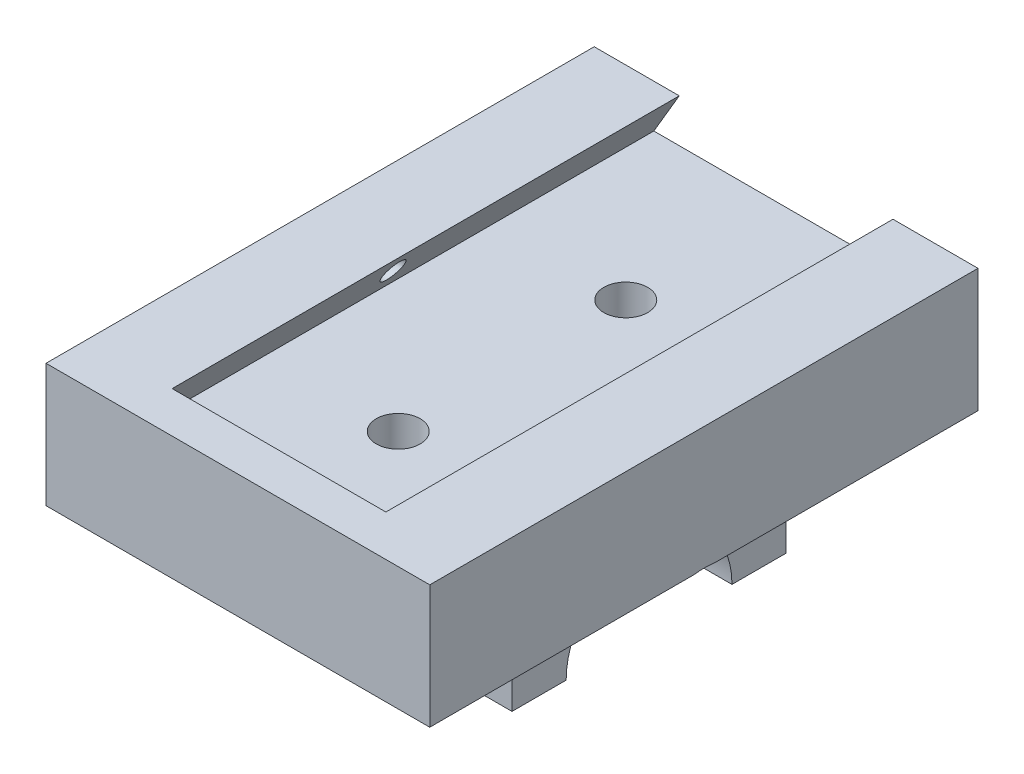
SolidWorks part; units mm, degrees
ref_plane "Front Plane" through (0, 0, 0) normal (0, 0, 1) x (1, 0, 0)
ref_plane "Top Plane" through (0, 0, 0) normal (0, 1, 0) x (1, 0, 0)
ref_plane "Right Plane" through (0, 0, 0) normal (1, 0, 0) x (0, 0, -1)
sketch "Sketch1" plane through (0, 0, 0) normal (0, 0, 1) x (1, 0, 0)
  line L0 (-28, 0) -> (28, 0)
  line L1 (28, 0) -> (28, 18)
  line L2 (28, 18) -> (-28, 18)
  line L3 (-28, 18) -> (-28, 0)
extrude "Channel Block" add sketch "Sketch1" along normal mid plane 80
sketch "Sketch2" plane through (0, 0, 0) normal (1, 0, 0) x (0, 0, -1)
  line L0 (-20, -12) -> (20, -12)
  line L1 (20, -12) -> (20, 0.5)
  line L2 (20, 0.5) -> (-20, 0.5)
  line L3 (-20, 0.5) -> (-20, -12)
extrude "Clamp Upper Half" add sketch "Sketch2" along normal mid plane 40
sketch "Sketch3" plane through (0, 0, 0) normal (0, 0, 1) x (1, 0, 0)
  line L0 (-15.3, 18.5) -> (15.3, 18.5)
  line L1 (15.3, 18.5) -> (19.3, 11.7)
  line L2 (19.3, 11.7) -> (-19.3, 11.7)
  line L3 (-19.3, 11.7) -> (-15.3, 18.5)
extrude "Dovetail Channel" cut sketch "Sketch3" against normal blind 41 and the other way blind 34
sketch "Sketch4" plane through (0, 0, 0) normal (1, 0, 0) x (0, 0, -1)
  circle A0 centre (0, -12) radius 12.1
extrude "Handlebar Bore" cut sketch "Sketch4" against normal through all and the other way through all
sketch "Sketch5" plane through (0, 0, 0) normal (0, 1, 0) x (1, 0, 0)
  circle A0 centre (0, -16.6) radius 3.2
  circle A1 centre (0, 16.6) radius 3.2
extrude "M5 Insert Holes" cut sketch "Sketch5" against normal through all and the other way through all
sketch "Sketch6" plane through (0, 0, 0) normal (1, 0, 0) x (0, 0, -1)
  circle A0 centre (0, 15) radius 1.65
extrude "Lock Screw Hole" cut sketch "Sketch6" against normal through all
equation "\"BrW\" = 56.0"
equation "\"BrL\" = 80.0"
equation "\"BrH\" = 18.0"
equation "\"RailW\" = 30.0"
equation "\"RailW2\" = 38.0"
equation "\"RailH\" = 6.0"
equation "\"Slide\" = 0.3"
equation "\"StopT\" = 6.0"
equation "\"TubeD\" = 22.2"
equation "\"Liner\" = 1.0"
equation "\"ClampW\" = 40.0"
equation "\"ClampZ\" = 20.0"
equation "\"ClampY\" = -12.0"
equation "\"CapT\" = 12.0"
equation "\"BoltZ\" = 16.6"
equation "\"InsertD\" = 6.4"
equation "\"InsertL\" = 10.0"
equation "\"BoltD\" = 5.5"
equation "\"LockY\" = 15.0"
equation "\"LockD\" = 3.3"
